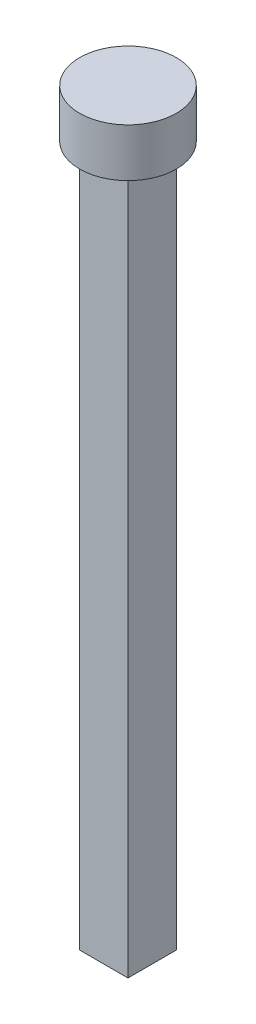
SolidWorks part; units mm, degrees
ref_plane "Front Plane" through (0, 0, 0) normal (0, 0, 1) x (1, 0, 0)
ref_plane "Top Plane" through (0, 0, 0) normal (0, 1, 0) x (1, 0, 0)
ref_plane "Right Plane" through (0, 0, 0) normal (1, 0, 0) x (0, 0, -1)
sketch "Sketch2" plane through (0, 0, 0) normal (0, 1, 0) x (1, 0, 0)
  circle A0 centre (0, 0) radius 20
extrude "Boss-Extrude1" add sketch "Sketch2" along normal blind 20
sketch "Sketch3" plane through (0, 0, 0) normal (0, -1, 0) x (1, 0, 0)
  line L1 (10, -10) -> (-10, -10)
  line L2 (10, -10) -> (10, 10)
  line L3 (10, 10) -> (-10, 10)
  line L4 (-10, -10) -> (-10, 10)
  line L5 (10, -10) -> (-10, 10) construction
  line L6 (10, 10) -> (-10, -10) construction
  point P0 (0, 0)
  dimension "D1" = 20
  dimension "D2" = 20
extrude "Boss-Extrude2" add sketch "Sketch3" along normal blind 290
sketch "Sketch4" plane through (0, -290, 0) normal (0, -1, 0) x (1, 0, 0)
  circle A0 centre (0, 0) radius 5
  dimension "D1" = 10
extrude "Cut-Extrude1" cut sketch "Sketch4" against normal blind 10
sketch "Sketch5" plane through (0, -290, 0) normal (0, -1, 0) x (1, 0, 0)
  point P0 (0, 0)
